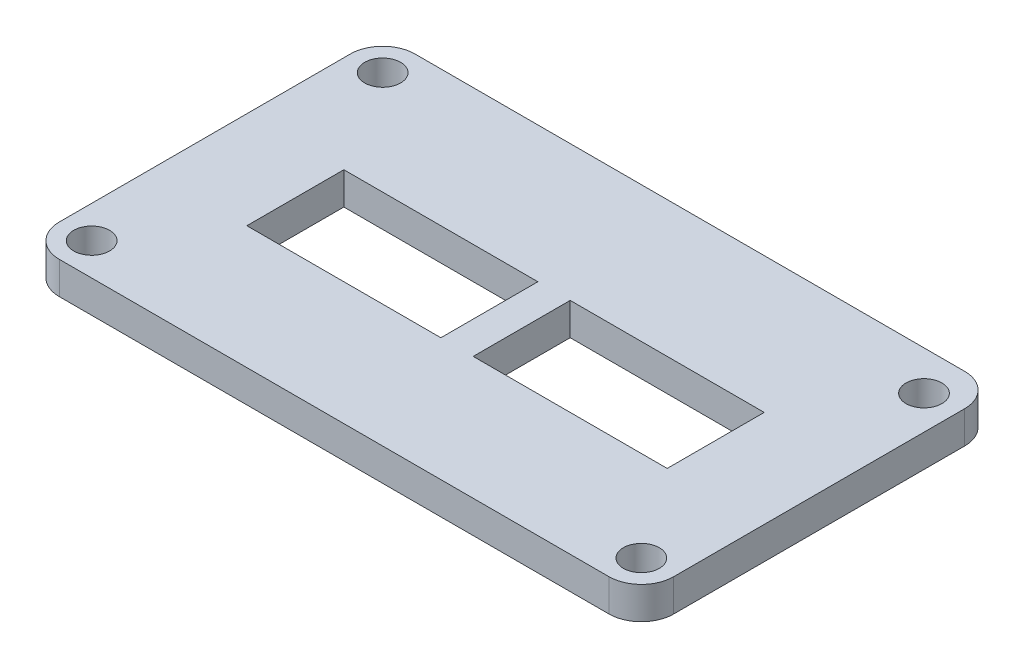
SolidWorks part; units mm, degrees
ref_plane "Front Plane" through (0, 0, 0) normal (0, 0, 1) x (1, 0, 0)
ref_plane "Top Plane" through (0, 0, 0) normal (0, 1, 0) x (1, 0, 0)
ref_plane "Right Plane" through (0, 0, 0) normal (1, 0, 0) x (0, 0, -1)
sketch "Sketch1" plane through (0, 0, 0) normal (0, 1, 0) x (1, 0, 0)
  line L0 (-24.13, -6.35) -> (24.13, -6.35) construction
  line L1 (-24.13, 13.97) -> (24.13, 13.97)
  line L2 (-24.13, 13.97) -> (-24.13, -13.97)
  line L3 (-24.13, -13.97) -> (24.13, -13.97)
  line L4 (24.13, 13.97) -> (24.13, -13.97)
  line L5 (0, -13.97) -> (0, 13.97) construction
  line L6 (-24.13, 0) -> (24.13, 0) construction
  point P0 (0, 0)
  dimension "D1" = 48.26
  dimension "D2" = 27.94
  dimension "D3" = 7.62
extrude "Boss-Extrude1" add sketch "Sketch1" along normal blind 2.54 contours L2 L1 L4 L3
sketch "Sketch2" plane through (0, 2.54, 0) normal (0, 1, 0) x (1, 0, 0)
  line L1 (-16.51, 3.302) -> (-1.27, 3.302)
  line L2 (-16.51, 3.302) -> (-16.51, -4.318)
  line L3 (-16.51, -4.318) -> (-1.27, -4.318)
  line L4 (-1.27, 3.302) -> (-1.27, -4.318)
  line L5 (1.27, 3.302) -> (16.51, 3.302)
  line L6 (1.27, 3.302) -> (1.27, -4.318)
  line L7 (1.27, -4.318) -> (16.51, -4.318)
  line L8 (16.51, 3.302) -> (16.51, -4.318)
  line L9 (-24.13, -13.97) -> (24.13, -13.97) construction
  dimension "D1" = 7.62
  dimension "D2" = 15.24
  dimension "D3" = 15.24
  dimension "D4" = 1.27
  dimension "D5" = 1.27
  dimension "D6" = 9.652
extrude "Cut-Extrude1" cut sketch "Sketch2" against normal blind 15.494
fillet "Fillet1" radius 2.54 4 edges at (24.13, 1.27, -13.97) (24.13, 1.27, 13.97) (-24.13, 1.27, 13.97) (-24.13, 1.27, -13.97)
hole_wizard "#34 (0.111) Diameter Hole1" positions "Sketch3" profile "Sketch4" hole size "#34" standard "ANSI Inch" end condition through all
sketch "Sketch3" plane through (0, 2.54, 0) normal (0, 1, 0) x (1, 0, 0)
  line L0 (-24.13, 11.43) -> (-24.13, -11.43) construction
  line L1 (-21.59, -13.97) -> (21.59, -13.97) construction
  circle A0 centre (-21.59, 11.43) radius 2.3241 construction
  point P0 (21.4836, 10.8783)
  point P2 (21.59, -11.43)
  point P4 (-21.59, -11.43)
  point P6 (-21.59, 11.43)
  dimension "D1" = 22.86
  dimension "D2" = 43.18
  dimension "D3" = 2.54
  dimension "D4" = 2.54
sketch "Sketch4" plane through (21.4836, 2.54, -10.8783) normal (1, 0, 0) x (0, 0, 1)
  line L0 (0, 0) -> (0, 2.54)
  line L1 (0, 2.54) -> (1.4097, 2.54)
  line L2 (1.4097, 2.54) -> (1.4097, 0)
  line L5 (1.4097, 0) -> (0, 0)
  line L11 (0, -6.35) -> (0, 107.95) construction
  dimension "Thru Hole Dia." = 2.8194
  dimension "Thru Hole Depth" = 2.54
